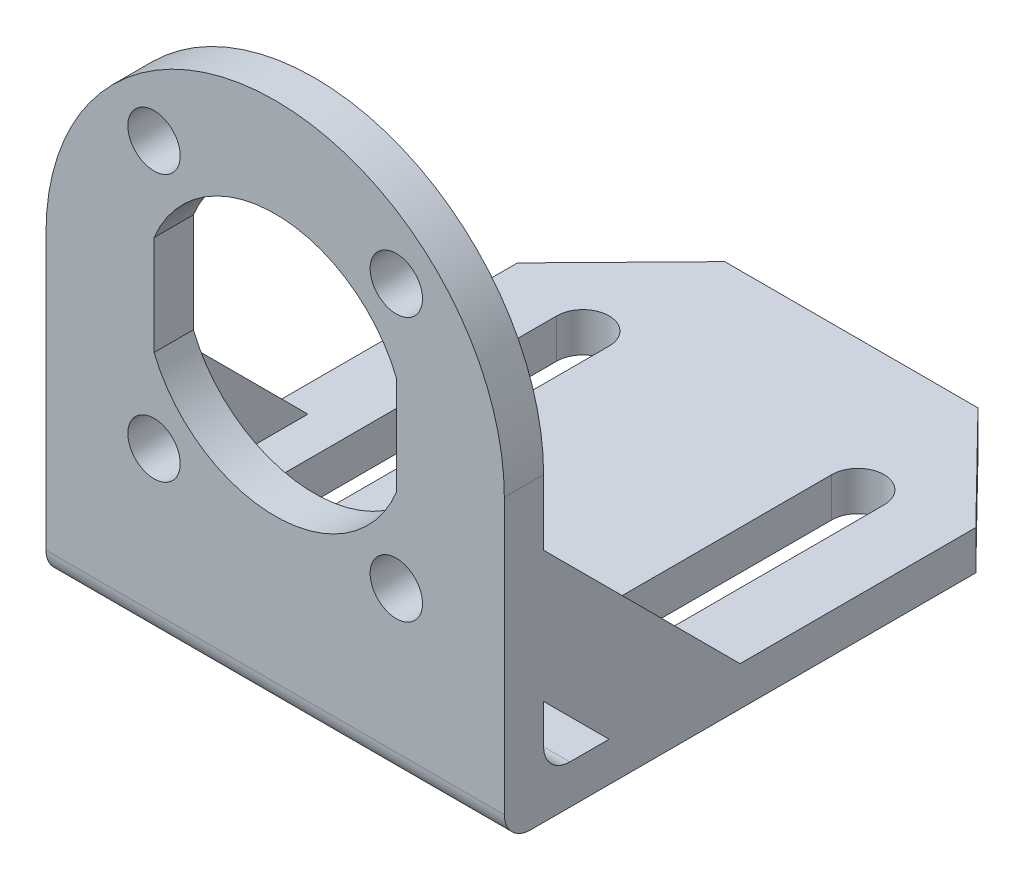
SolidWorks part; units mm, degrees
ref_plane "Front Plane" through (0, 0, 0) normal (0, 0, 1) x (1, 0, 0)
ref_plane "Top Plane" through (0, 0, 0) normal (0, 1, 0) x (1, 0, 0)
ref_plane "Right Plane" through (0, 0, 0) normal (1, 0, 0) x (0, 0, -1)
sketch "Sketch1" plane through (0, 0, 0) normal (0, 0, 1) x (1, 0, 0)
  line L0 (0, 0) -> (35, 0)
  line L1 (35, 0) -> (35, 20)
  line L2 (0, 20) -> (0, 0)
  line L3 (8.25, 23.7997) -> (8.25, 16.2003)
  line L4 (26.75, 23.7997) -> (26.75, 16.2003)
  line L5 (17.5, 30) -> (17.5, 20) construction
  line L6 (8.25, 20) -> (17.5, 20) construction
  arc A0 (35, 20) -> (0, 20) centre (17.5, 20) ccw
  arc A1 (8.25, 23.7997) -> (26.75, 23.7997) centre (17.5, 20) cw
  arc A3 (8.25, 16.2003) -> (26.75, 16.2003) centre (17.5, 20) ccw
  circle A8 centre (8.25, 30.2018) radius 2
  circle A9 centre (26.75, 30) radius 2
  circle A10 centre (8.25, 9.85) radius 2
  circle A11 centre (26.75, 9.85) radius 2
  point P12 (8.25, 20)
  dimension "D3" = 17.5
  dimension "D5" = 10
  dimension "D7" = 10
  dimension "D8" = 4
  dimension "D1" = 35
  dimension "D2" = 20
  dimension "D4" = 18.5
  dimension "D6" = 8.25
extrude "Boss-Extrude3" add sketch "Sketch1" along normal mid plane 3
sketch "Sketch5" plane through (0, 0, 1.5) normal (0, 0, 1) x (1, 0, 0)
  line L0 (0, 0) -> (35, 0)
  line L1 (35, 0) -> (35, -3)
  line L2 (35, -3) -> (0, -3)
  line L3 (0, -3) -> (0, 0)
  dimension "D1" = 3
extrude "Boss-Extrude4" add sketch "Sketch5" against normal blind 44
sketch "Sketch6" plane through (35, 0, 0) normal (1, 0, 0) x (0, 0, -1)
  line L0 (1.5, 15) -> (1.5, 5)
  line L1 (1.5, 0) -> (1.5, 20) construction
  line L2 (1.5, 5) -> (6.5, 0)
  line L3 (42.5, 0) -> (1.5, 0) construction
  line L4 (6.5, 0) -> (16.5, 0)
  line L5 (16.5, 0) -> (1.5, 15)
  dimension "D1" = 10
  dimension "D2" = 10
  dimension "D3" = 15
  dimension "D4" = 15
extrude "Boss-Extrude5" add sketch "Sketch6" against normal blind 2
ref_plane "Plane1" through (17.5, 0, 0) normal (1, 0, 0) x (0, 0, -1)
mirror "Mirror1" about plane through (17.5, 0, 0) normal (1, 0, 0) of "Boss-Extrude5"
sketch "Sketch7" plane through (0, 0, 0) normal (0, 1, 0) x (1, 0, 0)
  line L0 (0, 34.5) -> (7.83, 42.5)
  line L1 (0, 42.5) -> (0, 16.5) construction
  line L2 (35, 42.5) -> (0, 42.5) construction
  line L3 (7.83, 42.5) -> (27.17, 42.5)
  line L4 (27.17, 42.5) -> (35, 34.5)
  line L5 (35, 42.5) -> (35, 16.5) construction
  line L6 (7, 32.5) -> (7, 10.5) construction
  line L9 (9, 32.5) -> (9, 10.5)
  line L10 (5, 32.5) -> (5, 10.5)
  line L11 (28, 32.5) -> (28, 10.5) construction
  line L12 (30, 32.5) -> (30, 10.5)
  line L13 (26, 32.5) -> (26, 10.5)
  arc A0 (9, 32.5) -> (5, 32.5) centre (7, 32.5) ccw
  arc A1 (5, 10.5) -> (9, 10.5) centre (7, 10.5) ccw
  arc A2 (30, 32.5) -> (26, 32.5) centre (28, 32.5) ccw
  arc A3 (26, 10.5) -> (30, 10.5) centre (28, 10.5) ccw
  point P13 (7, 21.5)
  point P18 (28, 21.5)
  point P30 (7, 34.5)
  point P31 (28, 34.5)
  line M1 (0, 42.5) -> (0, 16.5)
  line M11 (35, 16.5) -> (35, 42.5)
  line M12 (35, 42.5) -> (0, 42.5)
  dimension "D3" = 2
  dimension "D1" = 19.34
  dimension "D2" = 22
  dimension "D4" = 10
  dimension "D5" = 5
  dimension "D6" = 5
extrude "Cut-Extrude1" cut sketch "Sketch7" against normal through all contours L10 A1 L9 A0 | L13 A3 L12 A2 | L4 M12 M11 | L0 M1 M12
fillet "Fillet1" radius 2 2 edges at (17.5, 0, -1.5) (17.5, -3, 1.5)
